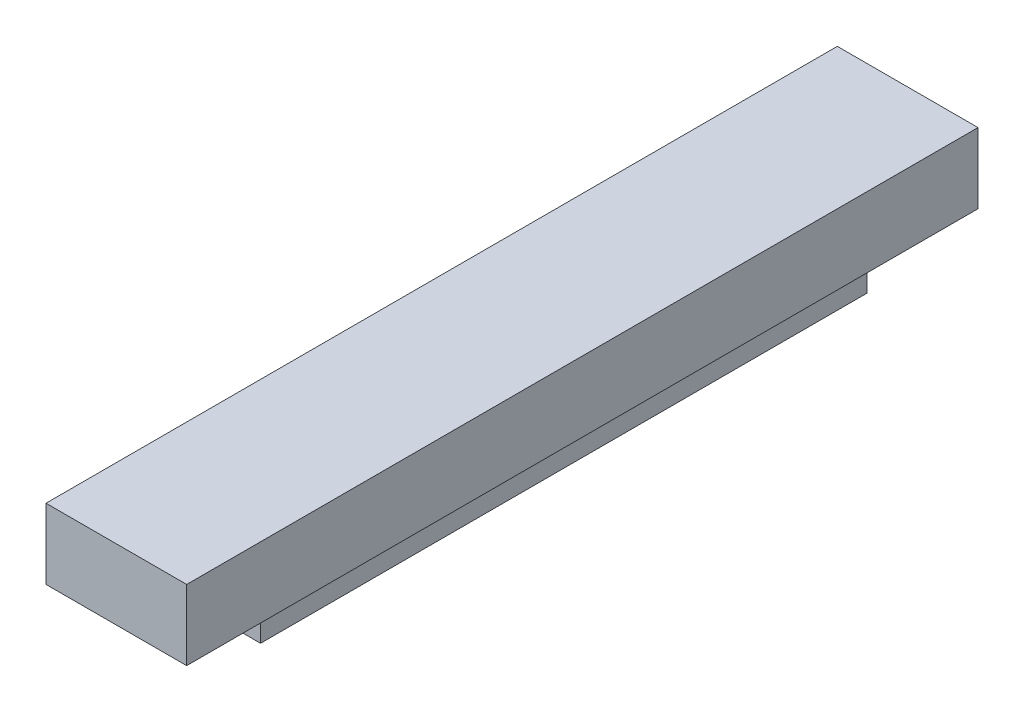
SolidWorks part; units mm, degrees
ref_plane "Alzado" through (0, 0, 0) normal (0, 0, 1) x (1, 0, 0)
ref_plane "Planta" through (0, 0, 0) normal (0, 1, 0) x (1, 0, 0)
ref_plane "Vista lateral" through (0, 0, 0) normal (1, 0, 0) x (0, 0, -1)
sketch "Croquis1" plane through (0, 0, 0) normal (0, 1, 0) x (1, 0, 0)
  line L1 (0, 0) -> (8, 0)
  line L2 (0, 0) -> (0, 45)
  line L3 (0, 45) -> (8, 45)
  line L4 (8, 0) -> (8, 45)
  dimension "D1" = 45
  dimension "D2" = 8
extrude "Saliente-Extruir1" add sketch "Croquis1" along normal blind 4
sketch "Croquis2" plane through (0, 0, 0) normal (0, -1, 0) x (1, 0, 0)
  line L0 (0, -45) -> (0, 0) construction
  line L1 (0, -7.2) -> (5, -7.2)
  line L2 (0, -7.2) -> (0, -41.7)
  line L3 (0, -41.7) -> (5, -41.7)
  line L4 (5, -7.2) -> (5, -41.7)
  line L5 (8, 0) -> (8, -45) construction
  line L6 (0, 0) -> (8, 0) construction
  dimension "D1" = 3
  dimension "D2" = 7.2
  dimension "D3" = 34.5
extrude "Saliente-Extruir2" add sketch "Croquis2" along normal blind 4
